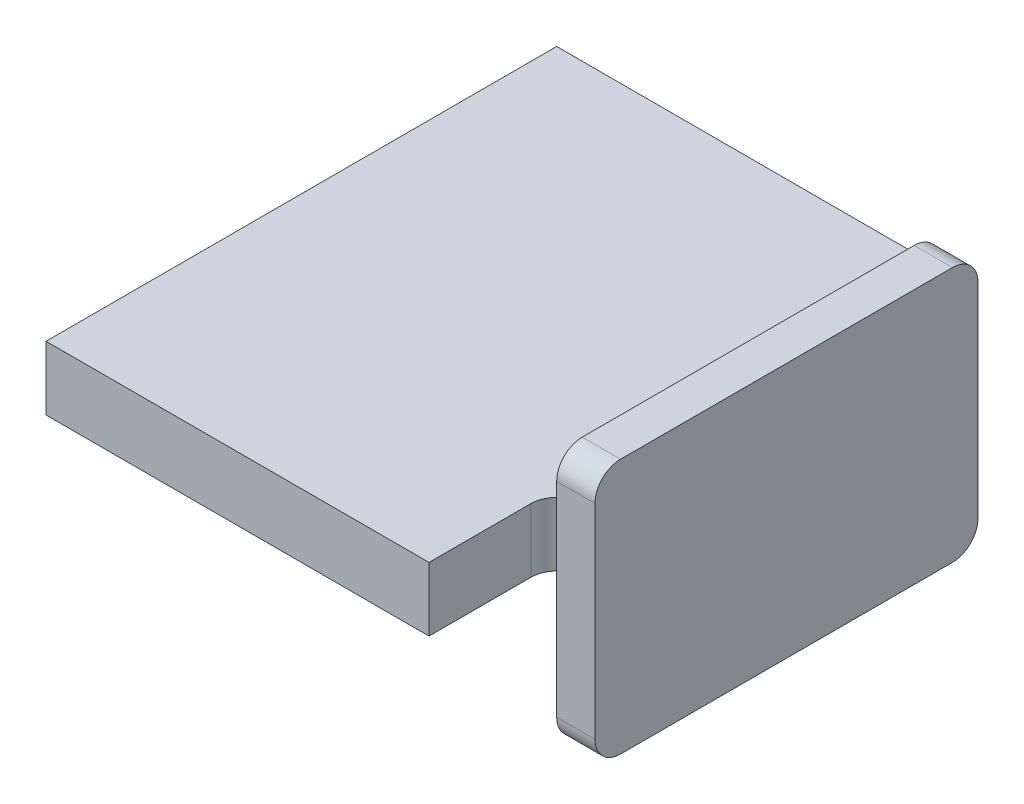
SolidWorks part; units mm, degrees
ref_plane "前视基准面" through (0, 0, 0) normal (0, 0, 1) x (1, 0, 0)
ref_plane "上视基准面" through (0, 0, 0) normal (0, 1, 0) x (1, 0, 0)
ref_plane "右视基准面" through (0, 0, 0) normal (1, 0, 0) x (0, 0, -1)
sketch "草图1" plane through (0, 0, 0) normal (1, 0, 0) x (0, 0, -1)
  line L1 (-10, 2.5) -> (10, 2.5)
  line L2 (-10, 2.5) -> (-10, -2.5)
  line L3 (-10, -2.5) -> (10, -2.5)
  line L4 (10, 2.5) -> (10, -2.5)
  line L5 (-10, 2.5) -> (10, -2.5) construction
  line L6 (-10, -2.5) -> (10, 2.5) construction
  point P0 (0, 0)
  dimension "D1" = 5
  dimension "D2" = 20
extrude "凸台-拉伸1" add sketch "草图1" against normal blind 35
sketch "草图2" plane through (0, 0, 0) normal (1, 0, 0) x (0, 0, -1)
  line L1 (-15, 10) -> (15, 10)
  line L2 (-15, 10) -> (-15, -10)
  line L3 (-15, -10) -> (15, -10)
  line L4 (15, 10) -> (15, -10)
  line L5 (-15, 10) -> (15, -10) construction
  line L6 (-15, -10) -> (15, 10) construction
  point P0 (0, 0)
  dimension "D1" = 20
  dimension "D2" = 30
extrude "凸台-拉伸2" add sketch "草图2" along normal blind 3
fillet "圆角1" radius 2 1 edges at (1.5, 10, -15)
fillet "圆角2" radius 2 1 edges at (1.5, 10, 15)
fillet "圆角3" radius 2 1 edges at (1.5, -10, -15)
fillet "圆角4" radius 2 1 edges at (1.5, -10, 15)
sketch "草图4" plane through (0, 0, 0) normal (0, 1, 0) x (1, 0, 0)
  line L0 (-71.4991, 0) -> (19.3429, 0) construction
  line L1 (-35, 20) -> (-5, 20)
  line L2 (-35, 20) -> (-35, -20)
  line L3 (-35, -20) -> (-5, -20)
  line L4 (-5, 20) -> (-5, -20)
  line L5 (0, 13) -> (0, -13) construction
  point P7 (-35, 0)
  dimension "D1" = 30
  dimension "D2" = 20
  dimension "D3" = 5
extrude "凸台-拉伸3" add sketch "草图4" along normal mid plane 5
fillet "圆角5" radius 2 1 edges at (-5, 0, -10)
fillet "圆角6" radius 2 1 edges at (-5, 0, 10)
